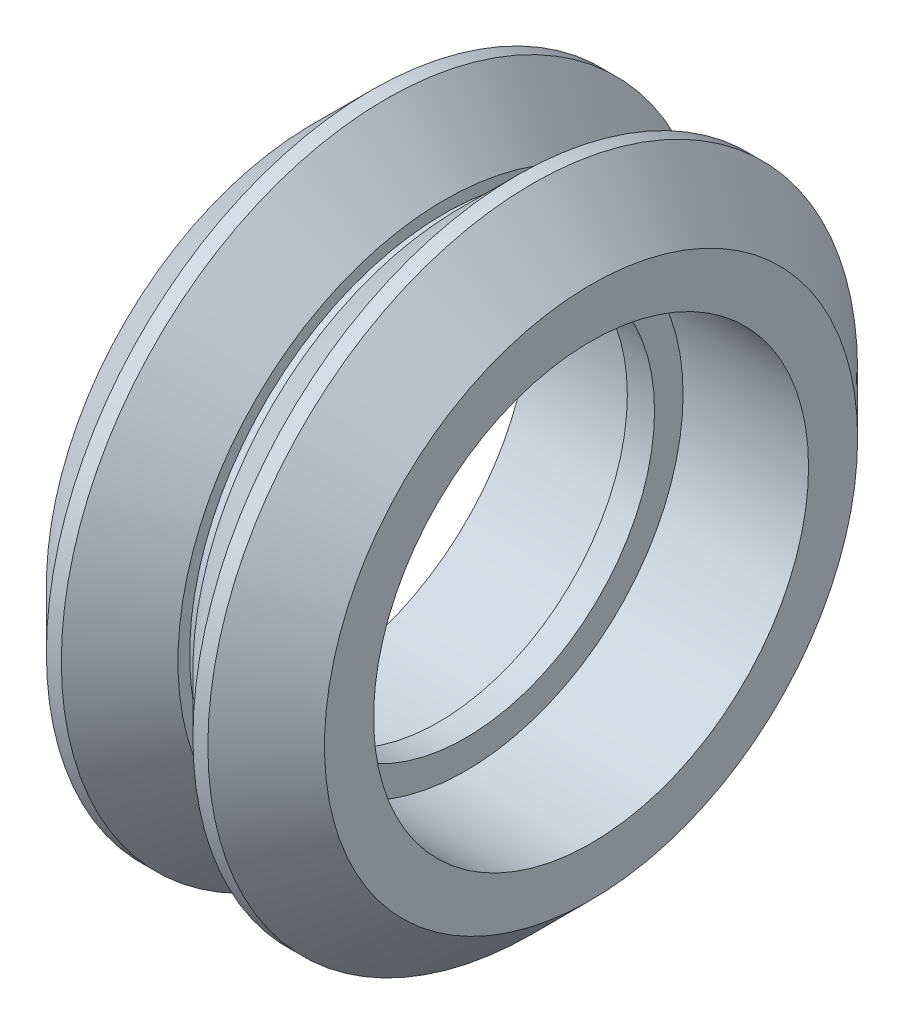
SolidWorks part; units mm, degrees
material "Delrin 2700 NC010, Low Viscosity Acetal Copolymer (SS)"
ref_plane "Front Plane" through (0, 0, 0) normal (0, 0, 1) x (1, 0, 0)
ref_plane "Top Plane" through (0, 0, 0) normal (0, 1, 0) x (1, 0, 0)
ref_plane "Right Plane" through (0, 0, 0) normal (1, 0, 0) x (0, 0, -1)
sketch "Sketch1" plane through (0, 0, 0) normal (0, 0, 1) x (1, 0, 0)
  line L0 (0.5, 6.95) -> (-0.5, 6.95)
  line L1 (-0.5, 6.95) -> (-0.5, 8)
  line L2 (-0.5, 8) -> (-5.115, 8)
  line L3 (-5.115, 8) -> (-5.115, 9.805)
  line L4 (-5.115, 9.805) -> (-2.97, 11.95)
  line L5 (-2.97, 11.95) -> (-2.42, 11.95)
  line L6 (0, 12) -> (0, 6.95) construction
  line L7 (5.115, 9.805) -> (2.97, 11.95)
  line L8 (5.115, 8) -> (5.115, 9.805)
  line L9 (0.5, 8) -> (5.115, 8)
  line L10 (0.5, 6.95) -> (0.5, 8)
  line L11 (0, 0) -> (-12.6359, 0) construction
  line L12 (-2.42, 11.95) -> (-0.275, 9.805)
  line L13 (-0.275, 9.805) -> (-0.275, 9.375)
  line L14 (-0.275, 9.375) -> (0.275, 9.375)
  line L15 (0.275, 9.805) -> (0.275, 9.375)
  line L16 (2.97, 11.95) -> (2.42, 11.95)
  line L17 (2.42, 11.95) -> (0.275, 9.805)
  point P20 (0, 9.375)
  dimension "D1" = 0.55
  dimension "D2" = 16
  dimension "D3" = 23.9
  dimension "D4" = 1
  dimension "D5" = 45
  dimension "D6" = 10.23
  dimension "D7" = 18.75
  dimension "D8" = 13.9
  dimension "D9" = 0.55
revolve "Revolve1" add sketch "Sketch1" angle 360 about L11
sketch "Sketch2" plane through (5.115, 0, 0) normal (1, 0, 0) x (0, 0, -1)
  line L0 (0, 9.805) -> (0, -9.805) construction
  circle A0 centre (0, 0) radius 9.805 construction
  point P5 (0, 0)
